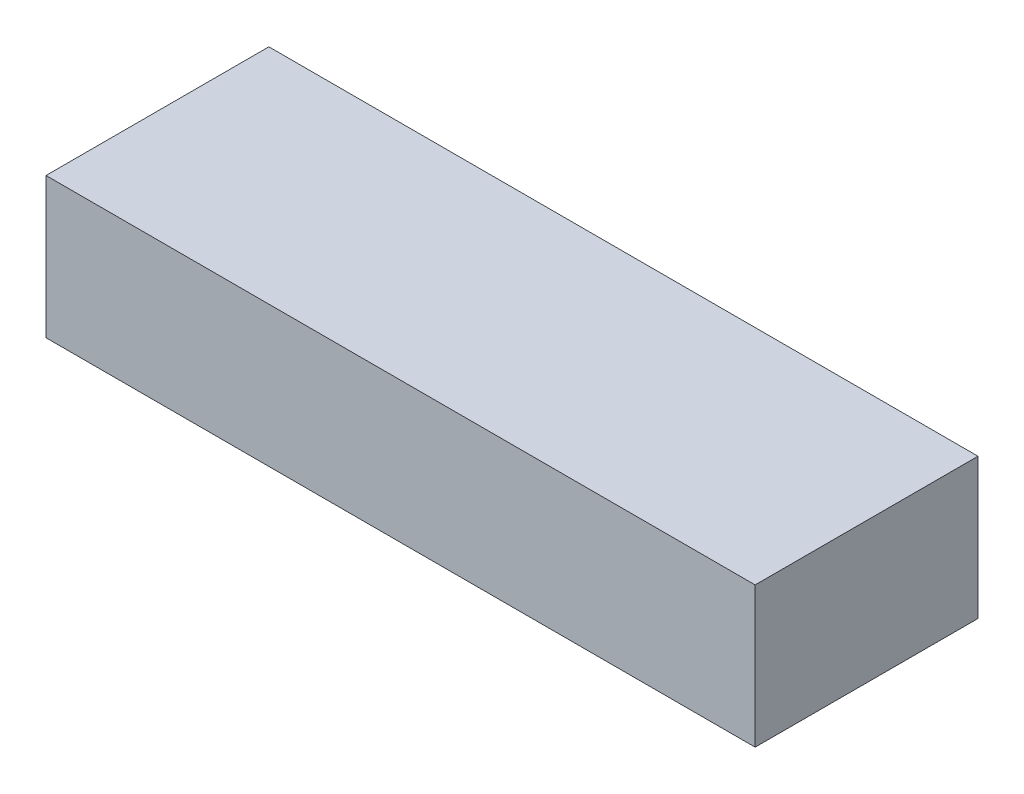
SolidWorks part; units mm, degrees
ref_plane "前基準面" through (0, 0, 0) normal (0, 0, 1) x (1, 0, 0)
ref_plane "上基準面" through (0, 0, 0) normal (0, 1, 0) x (1, 0, 0)
ref_plane "右基準面" through (0, 0, 0) normal (1, 0, 0) x (0, 0, -1)
sketch "草圖1" plane through (0, 0, 0) normal (0, 1, 0) x (1, 0, 0)
  line L1 (-70, -22) -> (70, -22)
  line L2 (-70, -22) -> (-70, 22)
  line L3 (-70, 22) -> (70, 22)
  line L4 (70, -22) -> (70, 22)
  line L5 (-70, -22) -> (70, 22) construction
  line L6 (-70, 22) -> (70, -22) construction
  point P0 (0, 0)
  dimension "D1" = 140
  dimension "D2" = 44
extrude "填料-伸長1" add sketch "草圖1" along normal blind 27.75
